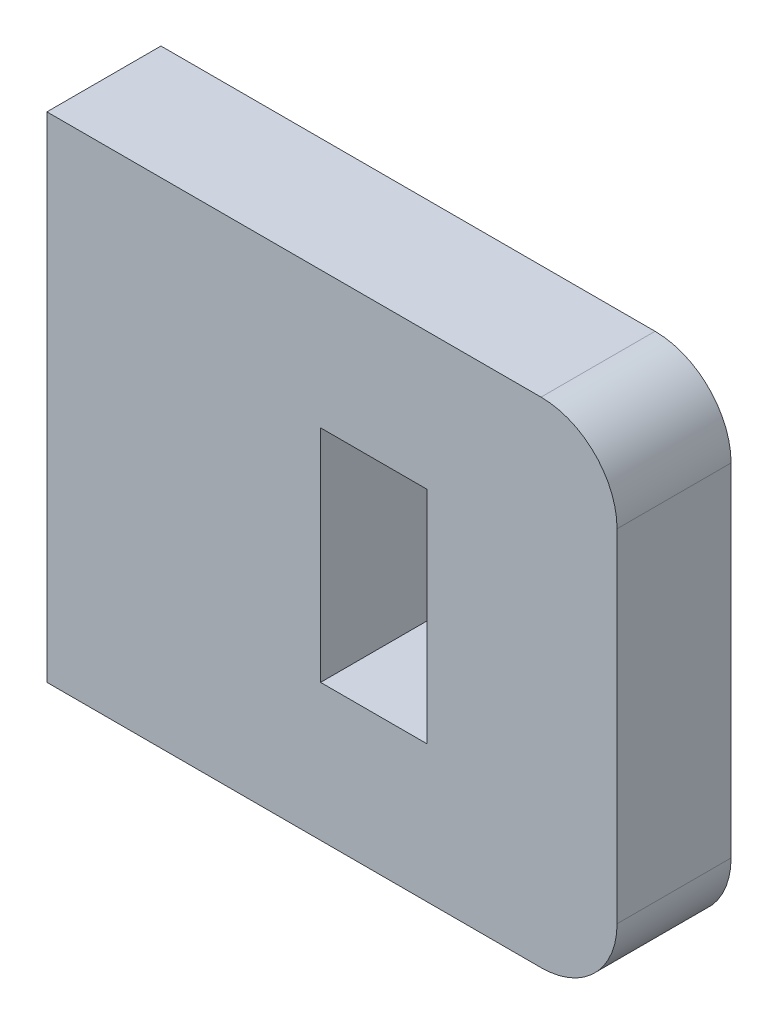
SolidWorks part; units mm, degrees
material "Balsa"
ref_plane "Alzado" through (0, 0, 0) normal (0, 0, 1) x (1, 0, 0)
ref_plane "Planta" through (0, 0, 0) normal (0, 1, 0) x (1, 0, 0)
ref_plane "Vista lateral" through (0, 0, 0) normal (1, 0, 0) x (0, 0, -1)
sketch "Croquis1" plane through (0, 0, 0) normal (0, 0, 1) x (1, 0, 0)
  line L1 (-4.5, -6.5) -> (10.5, -6.5)
  line L2 (-4.5, -6.5) -> (-4.5, 6.5)
  line L3 (-4.5, 6.5) -> (10.5, 6.5)
  line L4 (10.5, -6.5) -> (10.5, 6.5)
  line L5 (0, 0) -> (10.5, 6.5) construction
  line L6 (-3.0018, 1.8583) -> (10.5, -6.5) construction
  line L8 (-4.5, 6.5) -> (-1.5, 6.5)
  line L9 (-4.5, 6.5) -> (-4.5, 0.5)
  line L12 (-4.5, -6.5) -> (-1.5, -6.5)
  line L13 (-4.5, -6.5) -> (-4.5, -2.5)
  line L16 (2.7, -2.9) -> (5.5, -2.9)
  line L17 (2.7, -2.9) -> (2.7, 2.9)
  line L18 (2.7, 2.9) -> (5.5, 2.9)
  line L19 (5.5, -2.9) -> (5.5, 2.9)
  line L20 (2.7, -2.9) -> (5.5, 2.9) construction
  line L21 (2.7, 2.9) -> (5.5, -2.9) construction
  point P0 (0, 0)
  point P12 (4.1, 0)
  dimension "D1" = 13
  dimension "D2" = 15
  dimension "D6" = 2.8
  dimension "D7" = 5.8
  dimension "D8" = 0
  dimension "D9" = 5
extrude "Saliente-Extruir1" add sketch "Croquis1" along normal mid plane 3
fillet "Redondeo1" radius 2 2 edges at (10.5, 6.5, 0) (10.5, -6.5, 0)
